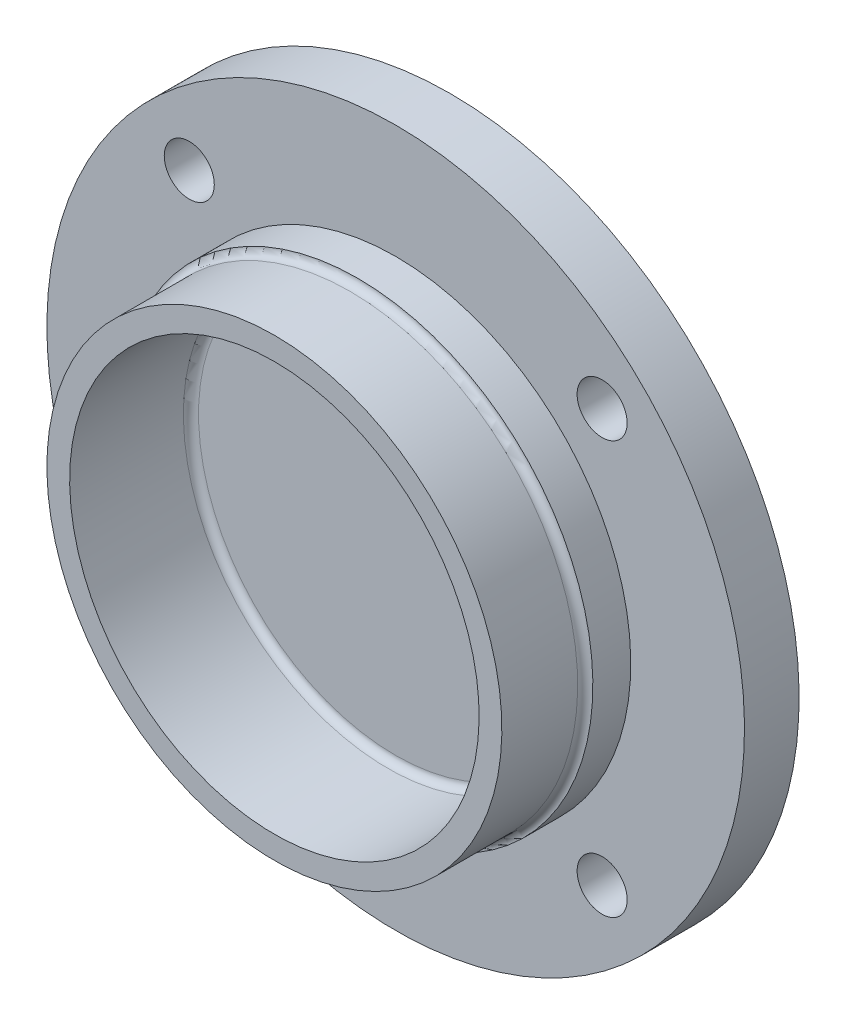
SolidWorks part; units mm, degrees
material "EN-GJL-300"
ref_plane "Front Plane" through (0, 0, 0) normal (0, 0, 1) x (1, 0, 0)
ref_plane "Top Plane" through (0, 0, 0) normal (0, 1, 0) x (1, 0, 0)
ref_plane "Right Plane" through (0, 0, 0) normal (1, 0, 0) x (0, 0, -1)
sketch "Sketch1" plane through (0, 0, 0) normal (1, 0, 0) x (0, 0, -1)
  line L0 (0, 0) -> (0, 26)
  line L1 (-1, 27) -> (-16, 27)
  line L2 (-16, 27) -> (-16, 30)
  line L3 (-5, 31) -> (0, 31)
  line L4 (0, 31) -> (0, 46)
  line L5 (0, 46) -> (7.2, 46)
  line L6 (7.2, 46) -> (7.2, 31)
  line L8 (5.2, 29) -> (5.2, 0)
  line L9 (5.2, 0) -> (0, 0)
  line L10 (7.2, 0) -> (-16, 0) construction
  line L11 (-16, 30) -> (-6, 30)
  line L12 (7.2, 31) -> (5.2, 29)
  arc A0 (-6, 30) -> (-5, 31) centre (-6, 31) ccw
  arc A2 (0, 26) -> (-1, 27) centre (-1, 26) ccw
  point P23 (0, 27)
  dimension "D3" = 1
  dimension "D10" = 1
  dimension "D6" = 2
  dimension "D2" = 31
  dimension "D4" = 46
  dimension "D5" = 2
  dimension "D7" = 7.2
  dimension "D8" = 27
  dimension "D9" = 5
  dimension "D11" = 16
revolve "Revolve1" add sketch "Sketch1" angle 360 about L10
hole_wizard "M6 Clearance Hole1" positions "Sketch2" profile "Sketch3" hole size "M6" standard "ISO" end condition up to next
sketch "Sketch2" plane through (0, 0, -7.2) normal (0, 0, -1) x (-1, 0, 0)
  line L0 (27.2236, 27.2236) -> (0, 0) construction
  line L3 (0, 38.5) -> (0, 0) construction
  circle A0 centre (0, 0) radius 38.5 construction
  point P0 (27.2236, 27.2236)
  dimension "D1" = 77
  dimension "D2" = 45
sketch "Sketch3" plane through (-27.2236, 27.2236, -7.2) normal (1, 0, 0) x (0, 1, 0)
  line L0 (0, 0) -> (0, 7.2)
  line L1 (0, 7.2) -> (3.3, 7.2)
  line L2 (3.3, 7.2) -> (3.3, 0)
  line L5 (3.3, 0) -> (0, 0)
  line L11 (0, -6.35) -> (0, 107.95) construction
  dimension "Thru Hole Dia." = 6.6
  dimension "Thru Hole Depth" = 7.2
pattern_circular "CirPattern1" count 4 over 360 about axis through (0, 0, 0) along (0, 0, 1) of "M6 Clearance Hole1"
equation "\"D.r\"= 52"
